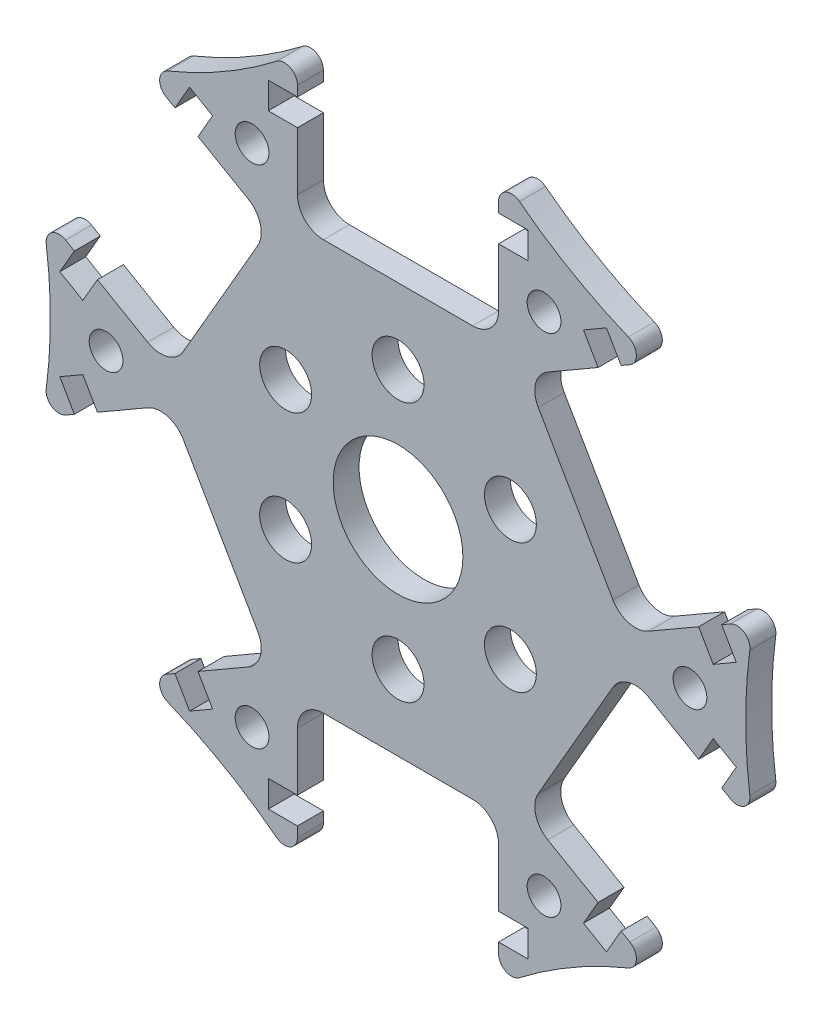
SolidWorks part; units mm, degrees
material "6061 合金"
ref_plane "Front" through (0, 0, 0) normal (0, 0, 1) x (1, 0, 0)
ref_plane "Top" through (0, 0, 0) normal (0, 1, 0) x (1, 0, 0)
ref_plane "Right" through (0, 0, 0) normal (1, 0, 0) x (0, 0, -1)
sketch "ｽｹｯﾁ1" plane through (0, 0, 0) normal (0, 0, 1) x (1, 0, 0)
  circle A0 centre (0, 0) radius 28.3
  dimension "D1" = 56.6
extrude "ﾎﾞｽ - 押し出し1" add sketch "ｽｹｯﾁ1" along normal blind 2
sketch "ｽｹｯﾁ2" plane through (0, 0, 2) normal (0, 0, 1) x (1, 0, 0)
  line L0 (0, 0) -> (0, 50000) construction
  line L1 (7.75, 24.325) -> (10, 24.325)
  line L2 (10, 24.325) -> (10, 22.275)
  line L3 (-7.75, 15.8) -> (-7.75, 22.275)
  line L4 (10, 22.275) -> (7.75, 22.275)
  line L5 (7.75, 27.2181) -> (7.75, 24.325)
  line L6 (7.75, 22.275) -> (7.75, 15.8)
  line L7 (7.75, 15.8) -> (-7.75, 15.8)
  line L8 (-7.75, 22.275) -> (-10, 22.275)
  line L9 (-10, 22.275) -> (-10, 24.325)
  line L10 (-10, 24.325) -> (-7.75, 24.325)
  line L11 (-7.75, 24.325) -> (-7.75, 27.2181)
  line L12 (0, 28.3) -> (16.8233, 28.3) construction
  line L13 (10, 23.3) -> (-10, 23.3) construction
  line L14 (0, 0) -> (28.3, 0) construction
  line L15 (24.9411, 5.4508) -> (26.0661, 3.5022)
  line L16 (26.0661, 3.5022) -> (24.2907, 2.4772)
  line L17 (9.8082, 14.6117) -> (15.4157, 17.8492)
  line L18 (24.2907, 2.4772) -> (23.1657, 4.4258)
  line L19 (27.4466, 6.8974) -> (24.9411, 5.4508)
  line L20 (23.1657, 4.4258) -> (17.5582, 1.1883)
  line L21 (17.5582, 1.1883) -> (9.8082, 14.6117)
  line L22 (15.4157, 17.8492) -> (14.2907, 19.7978)
  line L23 (14.2907, 19.7978) -> (16.0661, 20.8228)
  line L24 (16.0661, 20.8228) -> (17.1911, 18.8742)
  line L25 (17.1911, 18.8742) -> (19.6966, 20.3208)
  line L26 (25.1784, 2.9897) -> (15.1784, 20.3103) construction
  line L27 (17.1911, -18.8742) -> (16.0661, -20.8228)
  line L28 (16.0661, -20.8228) -> (14.2907, -19.7978)
  line L29 (17.5582, -1.1883) -> (23.1657, -4.4258)
  line L30 (14.2907, -19.7978) -> (15.4157, -17.8492)
  line L31 (19.6966, -20.3208) -> (17.1911, -18.8742)
  line L32 (15.4157, -17.8492) -> (9.8082, -14.6117)
  line L33 (9.8082, -14.6117) -> (17.5582, -1.1883)
  line L34 (23.1657, -4.4258) -> (24.2907, -2.4772)
  line L35 (24.2907, -2.4772) -> (26.0661, -3.5022)
  line L36 (26.0661, -3.5022) -> (24.9411, -5.4508)
  line L37 (24.9411, -5.4508) -> (27.4466, -6.8974)
  line L38 (15.1784, -20.3103) -> (25.1784, -2.9897) construction
  line L39 (-7.75, -24.325) -> (-10, -24.325)
  line L40 (-10, -24.325) -> (-10, -22.275)
  line L41 (7.75, -15.8) -> (7.75, -22.275)
  line L42 (-10, -22.275) -> (-7.75, -22.275)
  line L43 (-7.75, -27.2181) -> (-7.75, -24.325)
  line L44 (-7.75, -22.275) -> (-7.75, -15.8)
  line L45 (-7.75, -15.8) -> (7.75, -15.8)
  line L46 (7.75, -22.275) -> (10, -22.275)
  line L47 (10, -22.275) -> (10, -24.325)
  line L48 (10, -24.325) -> (7.75, -24.325)
  line L49 (7.75, -24.325) -> (7.75, -27.2181)
  line L50 (-10, -23.3) -> (10, -23.3) construction
  line L51 (-24.9411, -5.4508) -> (-26.0661, -3.5022)
  line L52 (-26.0661, -3.5022) -> (-24.2907, -2.4772)
  line L53 (-9.8082, -14.6117) -> (-15.4157, -17.8492)
  line L54 (-24.2907, -2.4772) -> (-23.1657, -4.4258)
  line L55 (-27.4466, -6.8974) -> (-24.9411, -5.4508)
  line L56 (-23.1657, -4.4258) -> (-17.5582, -1.1883)
  line L57 (-17.5582, -1.1883) -> (-9.8082, -14.6117)
  line L58 (-15.4157, -17.8492) -> (-14.2907, -19.7978)
  line L59 (-14.2907, -19.7978) -> (-16.0661, -20.8228)
  line L60 (-16.0661, -20.8228) -> (-17.1911, -18.8742)
  line L61 (-17.1911, -18.8742) -> (-19.6966, -20.3208)
  line L62 (-25.1784, -2.9897) -> (-15.1784, -20.3103) construction
  line L63 (-17.1911, 18.8742) -> (-16.0661, 20.8228)
  line L64 (-16.0661, 20.8228) -> (-14.2907, 19.7978)
  line L65 (-17.5582, 1.1883) -> (-23.1657, 4.4258)
  line L66 (-14.2907, 19.7978) -> (-15.4157, 17.8492)
  line L67 (-19.6966, 20.3208) -> (-17.1911, 18.8742)
  line L68 (-15.4157, 17.8492) -> (-9.8082, 14.6117)
  line L69 (-9.8082, 14.6117) -> (-17.5582, 1.1883)
  line L70 (-23.1657, 4.4258) -> (-24.2907, 2.4772)
  line L71 (-24.2907, 2.4772) -> (-26.0661, 3.5022)
  line L72 (-26.0661, 3.5022) -> (-24.9411, 5.4508)
  line L73 (-24.9411, 5.4508) -> (-27.4466, 6.8974)
  line L74 (-15.1784, 20.3103) -> (-25.1784, 2.9897) construction
  line L75 (0, 0) -> (8.6603, 5) construction
  line L76 (0, 0) -> (14.15, 24.5085) construction
  arc A0 (7.75, 27.2181) -> (-7.75, 27.2181) centre (0, 0) ccw
  circle A1 centre (0, 0) radius 28.3 construction
  circle A2 centre (0, 0) radius 5
  circle A3 centre (0, 0) radius 10 construction
  arc A4 (27.4466, 6.8974) -> (19.6966, 20.3208) centre (0, 0) ccw
  arc A5 (19.6966, -20.3208) -> (27.4466, -6.8974) centre (0, 0) ccw
  arc A6 (-7.75, -27.2181) -> (7.75, -27.2181) centre (0, 0) ccw
  arc A7 (-27.4466, -6.8974) -> (-19.6966, -20.3208) centre (0, 0) ccw
  arc A8 (-19.6966, 20.3208) -> (-27.4466, 6.8974) centre (0, 0) ccw
  circle A9 centre (8.6603, 5) radius 2
  circle A10 centre (8.6603, -5) radius 2
  circle A11 centre (0, -10) radius 2
  circle A12 centre (-8.6603, -5) radius 2
  circle A13 centre (-8.6603, 5) radius 2
  circle A14 centre (0, 10) radius 2
  circle A15 centre (0, 0) radius 22.5 construction
  circle A16 centre (11.25, 19.4856) radius 1.3
  circle A17 centre (22.5, 0) radius 1.3
  circle A18 centre (11.25, -19.4856) radius 1.3
  circle A19 centre (-11.25, -19.4856) radius 1.3
  circle A20 centre (-22.5, 0) radius 1.3
  circle A21 centre (-11.25, 19.4856) radius 1.3
  point P99 (0, 0)
  point P111 (0, 0)
  dimension "D1" = 15.5
  dimension "D6" = 10
  dimension "D7" = 20
  dimension "D9" = 30
  dimension "D10" = 4
  dimension "D13" = 45
  dimension "D14" = 2.6
  dimension "D2" = 20
  dimension "D3" = 2.05
  dimension "D4" = 12.5
  dimension "D5" = 5
  dimension "D12" = 60
  dimension "D8" = 6
  dimension "D11" = 6
extrude "ｶｯﾄ - 押し出し1" cut sketch "ｽｹｯﾁ2" against normal through all
sketch "ｽｹｯﾁ3" plane through (0, 0, 2) normal (0, 0, 1) x (1, 0, 0)
  line L0 (0, 0) -> (14.15, 24.5085) construction
  arc A0 (19.6966, 20.3208) -> (7.75, 27.2181) centre (0, 0) ccw construction
  arc A1 (7.75, 27.2181) -> (19.6966, 20.3208) centre (31.65, 54.8194) ccw
  arc A2 (19.6966, 20.3208) -> (7.75, 27.2181) centre (0, 0) ccw
  arc A3 (27.4466, 6.8974) -> (27.4466, -6.8974) centre (63.3, 0) ccw
  arc A4 (27.4466, -6.8974) -> (27.4466, 6.8974) centre (0, 0) ccw
  arc A5 (19.6966, -20.3208) -> (7.75, -27.2181) centre (31.65, -54.8194) ccw
  arc A6 (7.75, -27.2181) -> (19.6966, -20.3208) centre (0, 0) ccw
  arc A7 (-7.75, -27.2181) -> (-19.6966, -20.3208) centre (-31.65, -54.8194) ccw
  arc A8 (-19.6966, -20.3208) -> (-7.75, -27.2181) centre (0, 0) ccw
  arc A9 (-27.4466, -6.8974) -> (-27.4466, 6.8974) centre (-63.3, 0) ccw
  arc A10 (-27.4466, 6.8974) -> (-27.4466, -6.8974) centre (0, 0) ccw
  arc A11 (-19.6966, 20.3208) -> (-7.75, 27.2181) centre (-31.65, 54.8194) ccw
  arc A12 (-7.75, 27.2181) -> (-19.6966, 20.3208) centre (0, 0) ccw
  point P27 (0, 0)
  dimension "D1" = 35
  dimension "D2" = 6
extrude "ｶｯﾄ - 押し出し3" cut sketch "ｽｹｯﾁ3" against normal through all
fillet "ﾌｨﾚｯﾄ2" radius 2 12 edges at (-9.8082, 14.6117, 1) (-17.5582, -1.1883, 1) (-17.5582, 1.1883, 1) (-7.75, -15.8, 1) (-9.8082, -14.6117, 1) (9.8082, -14.6117, 1) (7.75, -15.8, 1) (17.5582, -1.1883, 1) (17.5582, 1.1883, 1) (9.8082, 14.6117, 1) (7.75, 15.8, 1) (-7.75, 15.8, 1)
fillet "ﾌｨﾚｯﾄ1" radius 1 12 edges at (19.6966, 20.3208, 1) (7.75, 27.2181, 1) (-19.6966, 20.3208, 1) (-7.75, 27.2181, 1) (-27.4466, 6.8974, 1) (-27.4466, -6.8974, 1) (-19.6966, -20.3208, 1) (-7.75, -27.2181, 1) (7.75, -27.2181, 1) (19.6966, -20.3208, 1) (27.4466, -6.8974, 1) (27.4466, 6.8974, 1)
